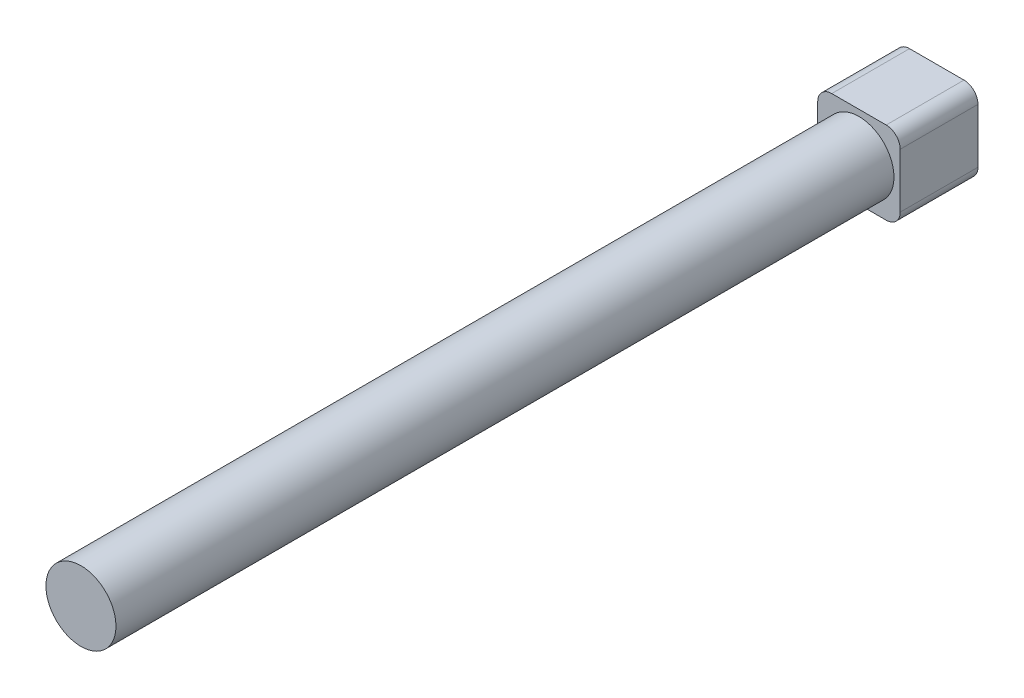
SolidWorks part; units mm, degrees
ref_plane "Front Plane" through (0, 0, 0) normal (0, 0, 1) x (1, 0, 0)
ref_plane "Top Plane" through (0, 0, 0) normal (0, 1, 0) x (1, 0, 0)
ref_plane "Right Plane" through (0, 0, 0) normal (1, 0, 0) x (0, 0, -1)
sketch "Sketch1" plane through (0, 0, 0) normal (0, 0, 1) x (1, 0, 0)
  line L0 (0, -1.8) -> (0, -8.8)
  line L1 (1.8, -10.6) -> (8.8, -10.6)
  line L2 (10.6, -8.8) -> (10.6, -1.8)
  line L3 (8.8, 0) -> (1.8, 0)
  arc A0 (10.6, -1.8) -> (8.8, 0) centre (8.8, -1.8) ccw
  arc A1 (10.6, -8.8) -> (8.8, -10.6) centre (8.8, -8.8) cw
  arc A2 (1.8, -10.6) -> (0, -8.8) centre (1.8, -8.8) cw
  arc A3 (0, -1.8) -> (1.8, 0) centre (1.8, -1.8) cw
  point P7 (10.6, 0)
  point P12 (0, -10.6)
  point P15 (0, 0)
  dimension "D3" = 1.8
  dimension "D4" = 1.8
  dimension "D1" = 10.6
  dimension "D2" = 10.6
extrude "Boss-Extrude1" add sketch "Sketch1" along normal blind 10
sketch "Sketch2" plane through (0, 0, 10) normal (0, 0, 1) x (1, 0, 0)
  circle A0 centre (5.3, -5.3) radius 4.5
extrude "Boss-Extrude2" add sketch "Sketch2" along normal blind 100
